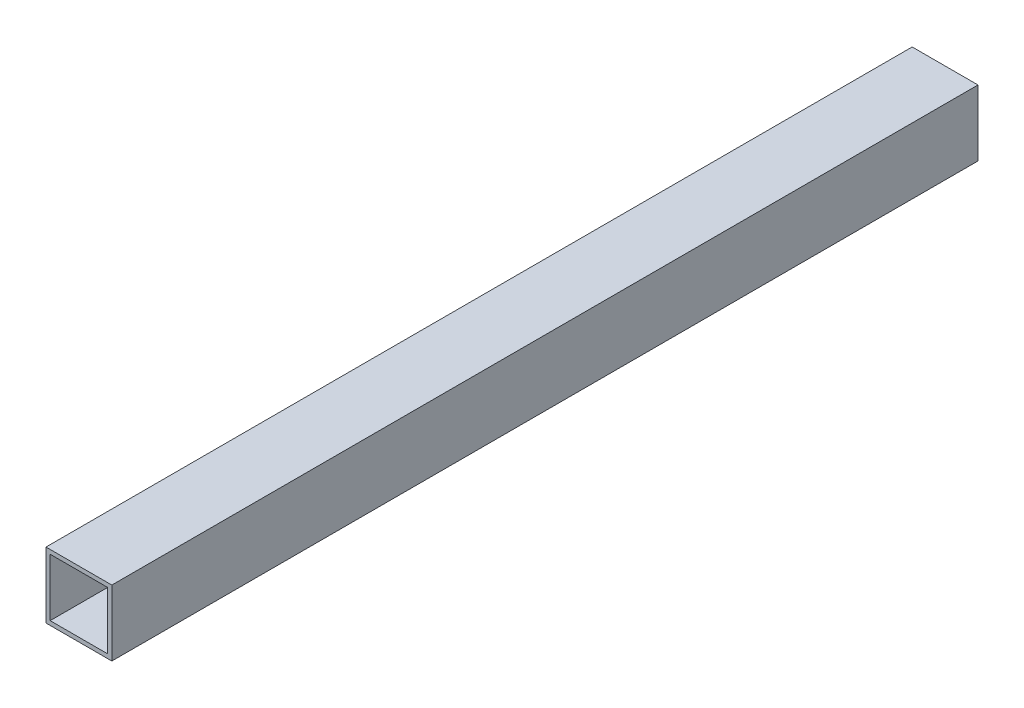
SolidWorks part; units mm, degrees
ref_plane "Front Plane" through (0, 0, 0) normal (0, 0, 1) x (1, 0, 0)
ref_plane "Top Plane" through (0, 0, 0) normal (0, 1, 0) x (1, 0, 0)
ref_plane "Right Plane" through (0, 0, 0) normal (1, 0, 0) x (0, 0, -1)
sketch "Sketch1" plane through (0, 0, 0) normal (0, 0, 1) x (1, 0, 0)
  line L0 (-8.3, 8.3) -> (-8.3, -8.3)
  line L1 (-9.5, 9.5) -> (9.5, 9.5)
  line L2 (-9.5, 9.5) -> (-9.5, -9.5)
  line L3 (-9.5, -9.5) -> (9.5, -9.5)
  line L4 (9.5, 9.5) -> (9.5, -9.5)
  line L5 (-9.5, 9.5) -> (9.5, -9.5) construction
  line L6 (-9.5, -9.5) -> (9.5, 9.5) construction
  line L7 (-8.3, -8.3) -> (8.3, -8.3)
  line L8 (8.3, 8.3) -> (8.3, -8.3)
  line L9 (-8.3, 8.3) -> (8.3, 8.3)
  point P0 (0, 0)
  dimension "D2" = 19
  dimension "D1" = 1.2
extrude "Boss-Extrude1" add sketch "Sketch1" along normal blind 250
